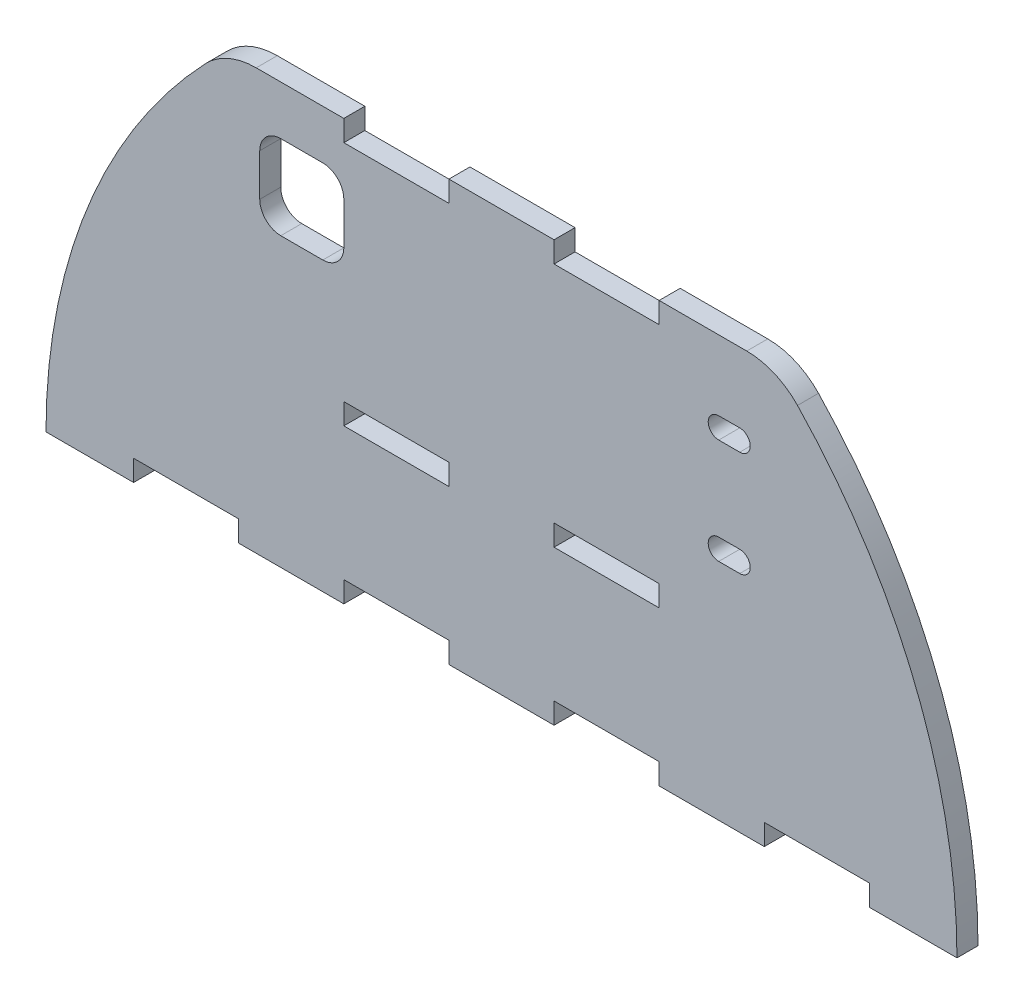
SolidWorks part; units mm, degrees
material "ABS PC"
ref_plane "Front Plane" through (0, 0, 0) normal (0, 0, 1) x (1, 0, 0)
ref_plane "Top Plane" through (0, 0, 0) normal (0, 1, 0) x (1, 0, 0)
ref_plane "Right Plane" through (0, 0, 0) normal (1, 0, 0) x (0, 0, -1)
sketch "Sketch1" plane through (0, 0, 0) normal (0, 0, 1) x (1, 0, 0)
  line L1 (35, 60) -> (-35, 60)
  line L2 (-35, 60) -> (-65, 60) construction
  line L3 (-65, 60) -> (-65, 0) construction
  line L4 (-65, 0) -> (65, 0)
  arc A0 (-42.2414, 56.8966) -> (-65, 0) centre (17.5, 0) ccw
  arc A1 (-35, 60) -> (-42.2414, 56.8966) centre (-35, 50) ccw
  arc A2 (65, 0) -> (42.2414, 56.8966) centre (-17.5, 0) ccw
  arc A3 (42.2414, 56.8966) -> (35, 60) centre (35, 50) ccw
  dimension "D4" = 10
  dimension "D1" = 60
  dimension "D2" = 70
  dimension "D3" = 130
extrude "Boss-Extrude1" add sketch "Sketch1" along normal blind 3
sketch "Sketch2" plane through (0, 0, 3) normal (0, 0, 1) x (1, 0, 0)
  line L0 (35, 60) -> (-35, 60) construction
  line L1 (-22.5, 60) -> (-7.5, 60)
  line L2 (-22.5, 60) -> (-22.5, 57)
  line L3 (-22.5, 57) -> (-7.5, 57)
  line L4 (-7.5, 60) -> (-7.5, 57)
  line L7 (-65, 0) -> (65, 0) construction
  line L8 (-52.5, 0) -> (-37.5, 0)
  line L9 (-52.5, 0) -> (-52.5, 3)
  line L10 (-52.5, 3) -> (-37.5, 3)
  line L11 (-37.5, 0) -> (-37.5, 3)
  line L12 (-37.5, 0) -> (-22.5, 0) construction
  line L13 (-22.5, 0) -> (-7.5, 0)
  line L14 (-22.5, 0) -> (-22.5, 3)
  line L15 (-35, 37.5) -> (-32, 37.5) construction
  line L16 (-35, 37.5) -> (-35, 22.5) construction
  line L17 (-35, 22.5) -> (-32, 22.5) construction
  line L18 (-32, 37.5) -> (-32, 22.5) construction
  line L20 (-35, 37.5) -> (-35, 60) construction
  line L21 (-35, 57) -> (-22.5, 57) construction
  line L22 (-22.5, 3) -> (-7.5, 3)
  line L23 (-7.5, 0) -> (-7.5, 3)
  line L24 (0, 0) -> (0, 3) construction
  line L26 (-7.5, 3) -> (7.5, 3) construction
  line L27 (-35, 22.5) -> (-35, 0) construction
  line L29 (-22.5, 25) -> (-7.5, 25)
  line L30 (-22.5, 25) -> (-22.5, 22)
  line L31 (-22.5, 22) -> (-7.5, 22)
  line L32 (-7.5, 25) -> (-7.5, 22)
  dimension "D1" = 3
  dimension "D2" = 15
  dimension "D3" = 22
extrude "Cut-Extrude1" cut sketch "Sketch2" against normal through all
mirror "Mirror1" about plane through (0, 0, 0) normal (1, 0, 0) of "Cut-Extrude1"
sketch "Sketch3" plane through (0, 0, 3) normal (0, 0, 1) x (1, 0, 0)
  line L1 (-31.5, 53) -> (-25.5, 53)
  line L2 (-34.5, 50) -> (-34.5, 44)
  line L3 (-31.5, 41) -> (-25.5, 41)
  line L4 (-22.5, 50) -> (-22.5, 44)
  line L5 (-22.5, 60) -> (-22.5, 57) construction
  line L7 (-7.5, 25) -> (-22.5, 25) construction
  arc A0 (-34.5, 50) -> (-31.5, 53) centre (-31.5, 50) cw
  arc A1 (-25.5, 53) -> (-22.5, 50) centre (-25.5, 50) cw
  arc A2 (-22.5, 44) -> (-25.5, 41) centre (-25.5, 44) cw
  arc A3 (-31.5, 41) -> (-34.5, 44) centre (-31.5, 44) cw
  point P6 (-34.5, 53)
  point P9 (-22.5, 53)
  point P14 (-34.5, 41)
  dimension "D3" = 3
  dimension "D4" = 3
  dimension "D1" = 12
  dimension "D2" = 12
  dimension "D5" = 28
extrude "Cut-Extrude2" cut sketch "Sketch3" against normal through all
sketch "Sketch4" plane through (0, 0, 3) normal (0, 0, 1) x (1, 0, 0)
  line L0 (31, 48.5) -> (34, 48.5) construction
  line L1 (31, 50) -> (34, 50)
  line L2 (31, 47) -> (34, 47)
  line L3 (31, 33.5) -> (34, 33.5) construction
  line L4 (31, 35) -> (34, 35)
  line L5 (31, 32) -> (34, 32)
  line L6 (32.5, 33.5) -> (32.5, 48.5) construction
  line L8 (32.5, 41) -> (22.5, 41) construction
  line L9 (22.5, 41) -> (22.5, 25) construction
  line L10 (22.5, 57) -> (22.5, 41) construction
  arc A0 (31, 50) -> (31, 47) centre (31, 48.5) ccw
  arc A1 (34, 47) -> (34, 50) centre (34, 48.5) ccw
  arc A2 (31, 35) -> (31, 32) centre (31, 33.5) ccw
  arc A3 (34, 32) -> (34, 35) centre (34, 33.5) ccw
  point P2 (32.5, 48.5)
  point P7 (32.5, 33.5)
  dimension "D2" = 1.5
  dimension "D1" = 3
  dimension "D3" = 15
  dimension "D4" = 10
extrude "Cut-Extrude3" cut sketch "Sketch4" against normal through all
